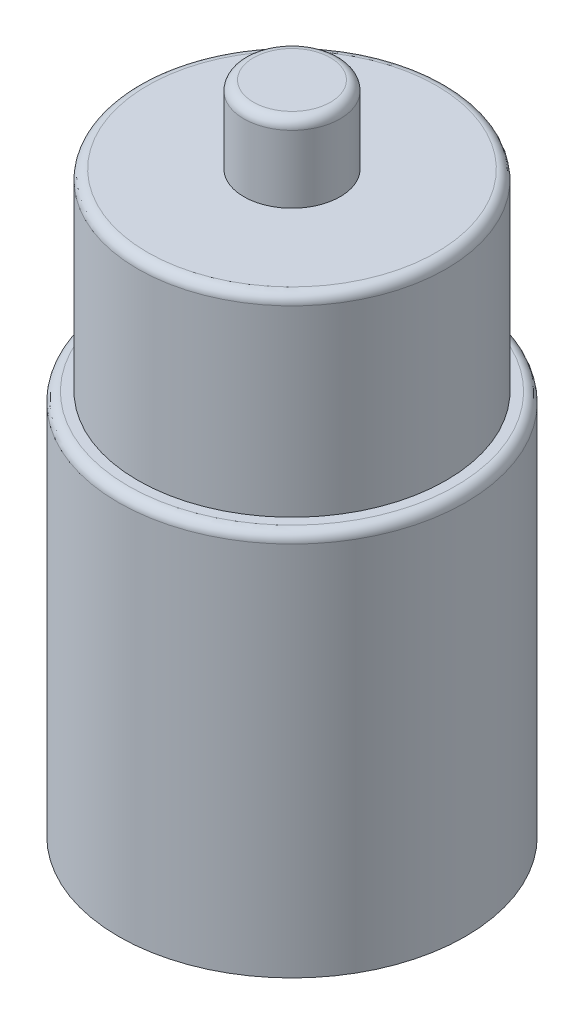
SolidWorks part; units mm, degrees
material "1060 Alloy"
ref_plane "Front Plane" through (0, 0, 0) normal (0, 0, 1) x (1, 0, 0)
ref_plane "Top Plane" through (0, 0, 0) normal (0, 1, 0) x (1, 0, 0)
ref_plane "Right Plane" through (0, 0, 0) normal (1, 0, 0) x (0, 0, -1)
sketch "Sketch1" plane through (0, 0, 0) normal (0, 1, 0) x (1, 0, 0)
  circle A0 centre (0, 0) radius 9
extrude "Boss-Extrude1" add sketch "Sketch1" along normal blind 20
sketch "Sketch2" plane through (0, 20, 0) normal (0, 1, 0) x (1, 0, 0)
  circle A0 centre (0, 0) radius 8
extrude "Boss-Extrude2" add sketch "Sketch2" along normal blind 10
cosmetic thread "Cosmetic Thread1" parameters "D1"=15, "D2"=15
sketch "Sketch3" plane through (0, 30, 0) normal (0, 1, 0) x (1, 0, 0)
  circle A0 centre (0, 0) radius 2.5
extrude "Boss-Extrude3" add sketch "Sketch3" along normal blind 4
fillet "Fillet1" radius 0.5 3 edges at (0, 34, 2.5) (0, 20, 9) (0, 30, 8)
